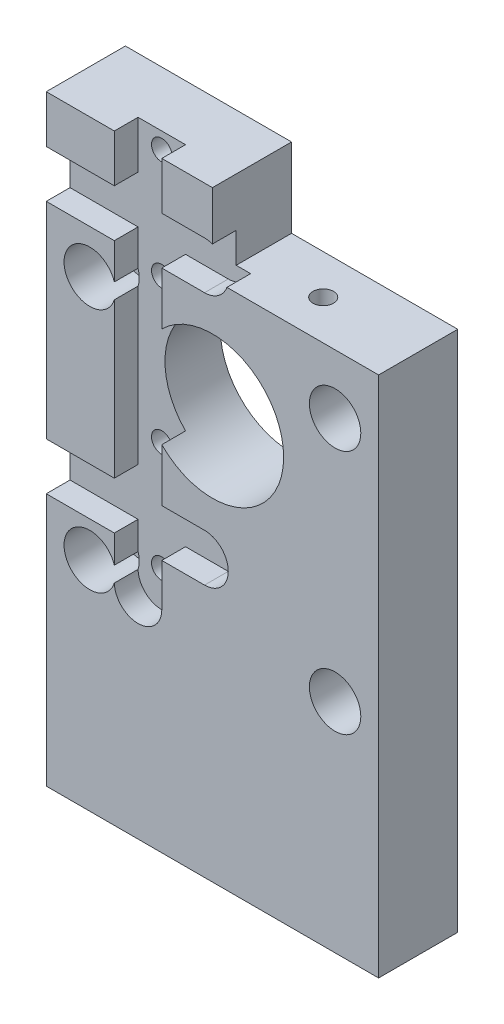
SolidWorks part; units mm, degrees
ref_plane "Front Plane" through (0, 0, 0) normal (0, 0, 1) x (1, 0, 0)
ref_plane "Top Plane" through (0, 0, 0) normal (0, 1, 0) x (1, 0, 0)
ref_plane "Right Plane" through (0, 0, 0) normal (1, 0, 0) x (0, 0, -1)
sketch "Sketch1" plane through (0, 0, 0) normal (0, 0, 1) x (1, 0, 0)
  line L1 (0, 0) -> (42, 0)
  line L2 (0, 0) -> (0, 66)
  line L3 (21, 66) -> (42, 66)
  line L4 (42, 0) -> (42, 66)
  line L8 (0, 66) -> (0, 76)
  line L9 (0, 76) -> (21, 76)
  line L10 (21, 66) -> (21, 76)
extrude "Boss-Extrude1" add sketch "Sketch1" along normal blind 10
sketch "Sketch2" plane through (0, 0, 10) normal (0, 0, 1) x (1, 0, 0)
  circle A0 centre (21, 51) radius 9
extrude "Cut-Extrude1" cut sketch "Sketch2" against normal up to next
sketch "Sketch3" plane through (0, 0, 10) normal (0, 0, 1) x (1, 0, 0)
  line L0 (8.6, 64) -> (8.6, 38)
  line L1 (8.6, 76) -> (14.6, 76)
  line L2 (8.6, 76) -> (8.6, 70)
  line L4 (14.6, 76) -> (14.6, 70)
  line L5 (14.6, 70) -> (20, 70)
  line L7 (0, 32) -> (8.6, 32)
  line L8 (0, 32) -> (0, 38)
  line L9 (0, 38) -> (8.6, 38)
  line L11 (14.6, 32) -> (14.6, 26.6)
  line L13 (0, 64) -> (8.6, 64)
  line L14 (0, 64) -> (0, 70)
  line L15 (0, 70) -> (8.6, 70)
  line L17 (14.6, 64) -> (20, 64)
  line L18 (14.6, 38) -> (20, 38)
  line L21 (14.6, 64) -> (14.6, 38)
  line L25 (8.6, 32) -> (8.6, 26.6)
  line L26 (14.6, 32) -> (20, 32)
  arc A0 (8.6, 26.6) -> (14.6, 26.6) centre (11.6, 26.6) ccw
  arc A1 (20, 32) -> (20, 38) centre (20, 35) ccw
  arc A2 (20, 64) -> (20, 70) centre (20, 67) ccw
extrude "Cut-Extrude2" cut sketch "Sketch3" against normal blind 3
sketch "Sketch4" plane through (0, 0, 10) normal (0, 0, 1) x (1, 0, 0)
  point P0 (5.5, 58.5)
  point P2 (36.5, 58.5)
  point P4 (5.5, 27.5)
  point P6 (36.5, 27.5)
hole_wizard "CBORE for M3 Pan Head Screw1" positions "Sketch4" profile "Sketch5" counterbore size "M3" standard "JIS" end condition through all
sketch "Sketch5" plane through (5.5, 58.5, 10) normal (1, 0, 0) x (0, -1, 0)
  line L0 (0, 0) -> (0, 10)
  line L1 (0, 10) -> (1.7, 10)
  line L3 (1.7, 10) -> (1.7, 6.5)
  line L4 (1.7, 6.5) -> (3.25, 6.5)
  line L5 (3.25, 6.5) -> (3.25, 0)
  line L7 (3.25, 0) -> (0, 0)
  line L11 (0, -6.35) -> (0, 107.95) construction
  dimension "Thru Hole Dia." = 3.4
  dimension "Thru Hole Depth" = 10
  dimension "C'Bore Dia." = 6.5
  dimension "C'Bore Depth" = 6.5
sketch "Sketch6" plane through (0, 0, 7) normal (0, 0, 1) x (1, 0, 0)
  point P0 (11.6, 73.9)
  point P2 (11.6, 60.1)
  point P4 (11.6, 41.9)
  point P6 (11.6, 28.1)
hole_wizard "M3x0.5 Tapped Hole1" positions "Sketch6" profile "Sketch7" tap size "M3x0.5" standard "JIS" end condition through all
sketch "Sketch7" plane through (11.6, 73.9, 7) normal (1, 0, 0) x (0, -1, 0)
  line L0 (0, 0) -> (0, 7)
  line L1 (0, 7) -> (1.3, 7)
  line L2 (1.3, 7) -> (1.3, 0)
  line L5 (1.3, 0) -> (0, 0)
  line L11 (0, -6.35) -> (0, 107.95) construction
  dimension "Thru Tap Drill Dia." = 2.6
  dimension "Thru Tap Drill Depth" = 7
cosmetic thread "Hole Thread1" parameters "D1"=5, "D2"=3
cosmetic thread "Hole Thread2" parameters "D1"=5, "D2"=3
cosmetic thread "Hole Thread3" parameters "D1"=5, "D2"=3
cosmetic thread "Hole Thread4" parameters "D1"=5, "D2"=3
hole_wizard "M3x0.5 Tapped Hole2" positions "Sketch8" profile "Sketch9" tap size "M3x0.5" standard "JIS"
sketch "Sketch8" plane through (0, 0, 0) normal (0, -1, 0) x (-1, 0, 0)
  point P0 (-32, -5)
  point P1 (-10, -5)
sketch "Sketch9" plane through (32, 0, 5) normal (1, 0, 0) x (0, 0, -1)
  line L0 (0, 0) -> (0, 9.7811)
  line L1 (0, 9.7811) -> (1.3, 9)
  line L2 (1.3, 9) -> (1.3, 0)
  line L5 (1.3, 0) -> (0, 0)
  line L10 (0, 9.7811) -> (-1.3, 9) construction
  line L11 (0, -6.35) -> (0, 107.95) construction
  dimension "Tap Drill Dia." = 2.6
  dimension "Tap Drill Depth" = 9
  dimension "Drill Angle" = 118
cosmetic thread "Hole Thread5" parameters "D1"=6, "D2"=3
cosmetic thread "Hole Thread6" parameters "D1"=6, "D2"=3
sketch "Sketch10" plane through (0, 66, 0) normal (0, 1, 0) x (1, 0, 0)
  point P0 (30, -5)
  point P4 (0, 0)
hole_wizard "M3x0.5 Tapped Hole3" positions "Sketch10" profile "Sketch11" tap size "M3x0.5" standard "JIS"
sketch "Sketch11" plane through (30, 66, 5) normal (1, 0, 0) x (0, 0, 1)
  line L0 (0, 0) -> (0, 9.7811)
  line L1 (0, 9.7811) -> (1.3, 9)
  line L2 (1.3, 9) -> (1.3, 0)
  line L5 (1.3, 0) -> (0, 0)
  line L10 (0, 9.7811) -> (-1.3, 9) construction
  line L11 (0, -6.35) -> (0, 107.95) construction
  dimension "Tap Drill Dia." = 2.6
  dimension "Tap Drill Depth" = 9
  dimension "Drill Angle" = 118
cosmetic thread "Hole Thread8" parameters "D1"=6, "D2"=3
